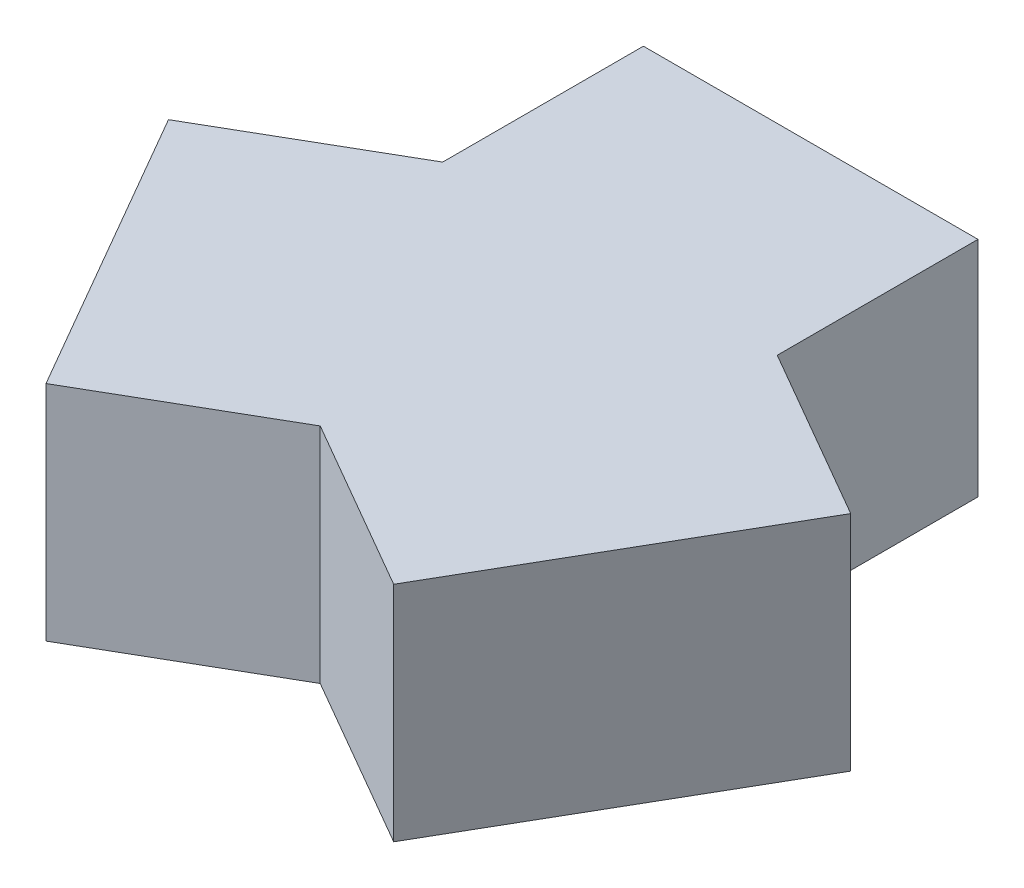
SolidWorks part; units mm, degrees
ref_plane "Front Plane" through (0, 0, 0) normal (0, 0, 1) x (1, 0, 0)
ref_plane "Top Plane" through (0, 0, 0) normal (0, 1, 0) x (1, 0, 0)
ref_plane "Right Plane" through (0, 0, 0) normal (1, 0, 0) x (0, 0, -1)
sketch "Sketch1" plane through (0, 0, 0) normal (0, 1, 0) x (1, 0, 0)
  line L0 (15.2942, 0.5) -> (7.5, 5)
  line L1 (7.5, 5) -> (7.5, 14)
  line L5 (0, -7.9904) -> (7.7942, -12.4904)
  line L7 (7.5, 5) -> (0, -7.9904) construction
  line L8 (7.5, 5) -> (-7.5, 5) construction
  line L9 (-7.5, 14) -> (7.5, 14)
  line L10 (15.2942, 0.5) -> (7.7942, -12.4904)
  line L12 (0, 30.0328) -> (0, -20.7177) construction
  line L13 (-7.5, 5) -> (0, -7.9904) construction
  line L14 (-15.2942, 0.5) -> (-7.7942, -12.4904)
  line L15 (0, -7.9904) -> (-7.7942, -12.4904)
  line L16 (-15.2942, 0.5) -> (-7.5, 5)
  line L17 (-7.5, 5) -> (-7.5, 14)
  point P6 (0, 5)
  point P9 (0, 14)
  dimension "D3" = 15
  dimension "D4" = 9
  dimension "D5" = 9
extrude "Boss-Extrude1" add sketch "Sketch1" along normal mid plane 10
